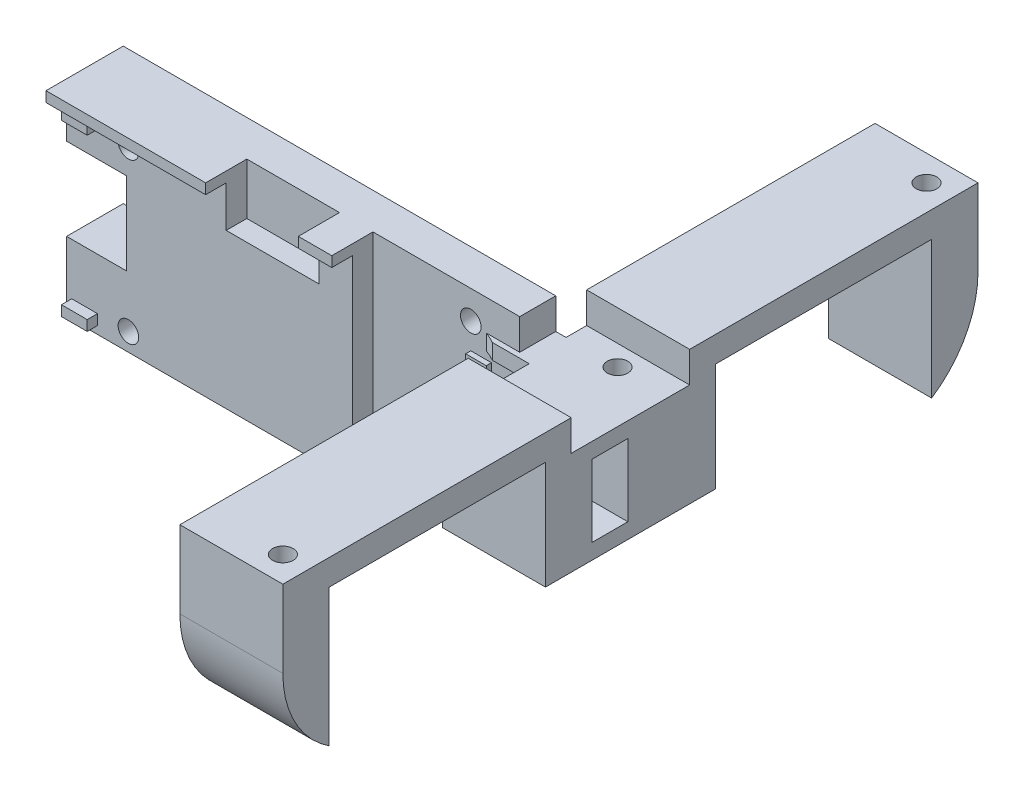
SolidWorks part; units mm, degrees
material "ABS"
ref_plane "Front Plane" through (0, 0, 0) normal (0, 0, 1) x (1, 0, 0)
ref_plane "Top Plane" through (0, 0, 0) normal (0, 1, 0) x (1, 0, 0)
ref_plane "Right Plane" through (0, 0, 0) normal (1, 0, 0) x (0, 0, -1)
sketch "Sketch1" plane through (0, 0, 0) normal (0, 1, 0) x (1, 0, 0)
  line L1 (-40.3176, 43.2333) -> (45.6824, 43.2333)
  line L2 (45.6824, 43.2333) -> (45.6824, -16.7667)
  line L3 (45.6824, -16.7667) -> (65.6824, -16.7667)
  line L4 (65.6824, -16.7667) -> (65.6824, 118.2333)
  line L7 (-40.3176, 43.2333) -> (-40.3176, 58.2333)
  line L8 (-40.3176, 58.2333) -> (45.6824, 58.2333)
  line L9 (45.6824, 58.2333) -> (45.6824, 118.2333)
  line L10 (45.6824, 118.2333) -> (65.6824, 118.2333)
  dimension "D1" = 20
  dimension "D2" = 60
  dimension "D3" = 86
  dimension "D4" = 15
  dimension "D5" = 60
  dimension "D6" = 20
extrude "Boss-Extrude1" add sketch "Sketch1" along normal blind 35
sketch "Sketch2" plane through (65.6824, 0, 0) normal (1, 0, 0) x (0, 0, -1)
  line L1 (-7.7667, 30) -> (34.2333, 30)
  line L2 (-7.7667, 30) -> (-7.7667, 9)
  line L3 (-7.7667, 9) -> (34.2333, 9)
  line L4 (34.2333, 30) -> (34.2333, 9)
  line L5 (-16.7667, 35) -> (-16.7667, 0) construction
  line L6 (50.7333, 24.6294) -> (50.7333, 59.3446) construction
  line L7 (-16.7667, 0) -> (118.2333, 0) construction
  line L9 (109.2333, 9) -> (67.2333, 9)
  line L10 (109.2333, 30) -> (109.2333, 9)
  line L11 (109.2333, 30) -> (67.2333, 30)
  line L12 (67.2333, 30) -> (67.2333, 9)
  dimension "D1" = 21
  dimension "D2" = 42
  dimension "D3" = 9
  dimension "D4" = 9
  dimension "D5" = 7.5
extrude "Cut-Extrude1" cut sketch "Sketch2" against normal up to next
sketch "Sketch3" plane through (45.6824, 0, 0) normal (-1, 0, 0) x (0, 0, 1)
  line L0 (7.7667, 9) -> (7.7667, 30) construction
  line L1 (-34.2333, 9) -> (7.7667, 9) construction
  line L2 (-50.7333, 32.1987) -> (-50.7333, 60.1119) construction
  line L3 (-43.2333, 35) -> (-43.2333, 0) construction
  circle A0 centre (11.2667, 24.75) radius 2
  circle A1 centre (11.2667, 15.25) radius 2
  circle A2 centre (-37.7333, 24.75) radius 2
  circle A3 centre (-37.7333, 15.25) radius 2
  circle A4 centre (-112.7333, 24.75) radius 2
  circle A5 centre (-112.7333, 15.25) radius 2
  circle A6 centre (-63.7333, 15.25) radius 2
  circle A7 centre (-63.7333, 24.75) radius 2
  dimension "D1" = 4
  dimension "D2" = 49
  dimension "D3" = 9.5
  dimension "D4" = 3.5
  dimension "D5" = 6.25
  dimension "D6" = 7.5
extrude "Cut-Extrude2" cut sketch "Sketch3" against normal blind 10
fillet "Fillet1" radius 20 2 edges at (55.6824, 0, 16.7667) (55.6824, 0, -118.2333)
sketch "Sketch6" plane through (65.6824, 0, 0) normal (1, 0, 0) x (0, 0, -1)
  line L0 (34.2333, 9) -> (34.2333, 30) construction
  line L1 (-7.7667, 9) -> (34.2333, 9)
  line L2 (-7.7667, 9) -> (-7.7667, 0)
  line L3 (-7.7667, 0) -> (34.2333, 0)
  line L4 (34.2333, 9) -> (34.2333, 0)
  line L5 (3.2333, 0) -> (98.2333, 0) construction
  line L6 (50.7333, 24.0053) -> (50.7333, 51.0852) construction
  line L7 (67.2333, 9) -> (67.2333, 0)
  line L8 (109.2333, 9) -> (67.2333, 9)
  line L9 (109.2333, 0) -> (67.2333, 0)
  line L10 (109.2333, 9) -> (109.2333, 0)
  dimension "D1" = 7.5
extrude "Cut-Extrude5" cut sketch "Sketch6" against normal up to next
sketch "Sketch8" plane through (0, 0, 0) normal (0, -1, 0) x (1, 0, 0)
  line L1 (45.6824, -67.2333) -> (45.6824, -58.2333) construction
  line L2 (45.6824, -67.2333) -> (65.6824, -67.2333) construction
  line L3 (65.6824, -34.2333) -> (65.6824, -67.2333) construction
  line L4 (45.6824, -34.2333) -> (65.6824, -34.2333) construction
  line L5 (45.6824, -43.2333) -> (45.6824, -34.2333) construction
  line L9 (45.6824, -67.2333) -> (45.6824, -58.2333)
  line L10 (45.6824, -67.2333) -> (65.6824, -67.2333)
  line L11 (65.6824, -34.2333) -> (65.6824, -67.2333)
  line L12 (45.6824, -34.2333) -> (65.6824, -34.2333)
  line L13 (45.6824, -43.2333) -> (45.6824, -34.2333)
  line L16 (45.6824, -43.2333) -> (25.6824, -43.2333)
  line L17 (-40.3176, -43.2333) -> (45.6824, -43.2333) construction
  line L18 (25.6824, -43.2333) -> (25.6824, -58.2333)
  line L19 (45.6824, -58.2333) -> (-40.3176, -58.2333) construction
  line L20 (25.6824, -58.2333) -> (45.6824, -58.2333)
  dimension "D1" = 20
extrude "Cut-Extrude7" cut sketch "Sketch8" against normal blind 9
sketch "Sketch9" plane through (0, 9, 0) normal (0, -1, 0) x (1, 0, 0)
  line L1 (65.6824, -34.2333) -> (45.6824, -34.2333) construction
  line L2 (65.6824, -67.2333) -> (65.6824, -34.2333) construction
  line L3 (45.6824, -67.2333) -> (65.6824, -67.2333) construction
  circle A0 centre (55.6824, -42.2333) radius 2
  circle A1 centre (55.6824, -59.2333) radius 2
  dimension "D4" = 10
  dimension "D5" = 8
  dimension "D6" = 8
extrude "Cut-Extrude8" cut sketch "Sketch9" against normal blind 10
sketch "Sketch10" plane through (0, 35, 0) normal (0, 1, 0) x (1, 0, 0)
  line L0 (45.6824, 62.2333) -> (65.6824, 62.2333)
  line L1 (45.6824, 118.2333) -> (45.6824, 58.2333) construction
  line L2 (65.6824, -16.7667) -> (65.6824, 118.2333) construction
  line L3 (65.6824, 62.2333) -> (65.6824, 39.2333)
  line L4 (65.6824, 39.2333) -> (45.6824, 39.2333)
  line L5 (45.6824, 43.2333) -> (45.6824, -16.7667) construction
  line L7 (45.6824, 39.2333) -> (45.6824, 43.2333)
  line L8 (45.6824, 43.2333) -> (43.6824, 43.2333)
  line L9 (-40.3176, 43.2333) -> (45.6824, 43.2333) construction
  line L10 (43.6824, 43.2333) -> (43.6824, 58.2333)
  line L11 (45.6824, 58.2333) -> (-40.3176, 58.2333) construction
  line L12 (43.6824, 58.2333) -> (45.6824, 58.2333)
  line L13 (45.6824, 58.2333) -> (45.6824, 62.2333)
  dimension "D1" = 5
  dimension "D2" = 5
  dimension "D3" = 2
extrude "Cut-Extrude9" cut sketch "Sketch10" against normal blind 6
sketch "Sketch11" plane through (0, 29, 0) normal (0, 1, 0) x (1, 0, 0)
  line L0 (45.6824, 62.2333) -> (45.6824, 58.2333) construction
  circle A0 centre (55.6824, 58.2333) radius 2
  circle A1 centre (55.6824, 43.2333) radius 2
  dimension "D1" = 4
  dimension "D2" = 10
  dimension "D5" = 0
extrude "Cut-Extrude10" cut sketch "Sketch11" against normal blind 9
sketch "Sketch12" plane through (0, 35, 0) normal (0, 1, 0) x (1, 0, 0)
  line L0 (65.6824, 118.2333) -> (45.6824, 118.2333) construction
  line L1 (45.6824, -16.7667) -> (65.6824, -16.7667) construction
  line L2 (65.6824, -16.7667) -> (65.6824, 39.2333) construction
  line L3 (65.6824, 62.2333) -> (65.6824, 118.2333) construction
  circle A0 centre (60.6824, -11.7667) radius 2
  circle A1 centre (60.6824, 113.2333) radius 2
  dimension "D2" = 4
  dimension "D1" = 5
  dimension "D3" = 5
  dimension "D4" = 5
  dimension "D5" = 5
extrude "Cut-Extrude11" cut sketch "Sketch12" against normal blind 10
sketch "Sketch14" plane through (0, 0, -43.2333) normal (0, 0, 1) x (1, 0, 0)
  line L0 (-40.3176, 35) -> (-40.3176, 0) construction
  line L1 (-40.3176, 33) -> (44.6824, 33)
  line L2 (-40.3176, 33) -> (-40.3176, 0)
  line L3 (-40.3176, 0) -> (44.6824, 0)
  line L4 (44.6824, 33) -> (44.6824, 0)
  line L5 (-40.3176, 0) -> (25.6824, 0) construction
  line L7 (-40.3176, 35) -> (43.6824, 35) construction
  dimension "D1" = 85
  dimension "D2" = 2
extrude "Cut-Extrude13" cut sketch "Sketch14" against normal blind 4
sketch "Sketch15" plane through (0, 0, -47.2333) normal (0, 0, 1) x (1, 0, 0)
  line L1 (15.6824, 20) -> (43.6824, 20)
  line L3 (15.6824, 0) -> (43.6824, 0)
  line L4 (43.6824, 20) -> (43.6824, 0)
  line L5 (43.6824, 29) -> (43.6824, 33) construction
  line L6 (-40.3176, 0) -> (25.6824, 0) construction
  line L13 (15.6824, 20) -> (15.6824, 0)
  line L14 (-40.3176, 33) -> (-40.3176, 0) construction
  point P0 (14.6824, 18.5247)
  point P7 (14.6824, 8)
  point P10 (18.6824, 8)
  point P11 (15.265, 8)
  dimension "D1" = 20
  dimension "D3" = 0
  dimension "D5" = 56
extrude "Cut-Extrude14" cut sketch "Sketch15" against normal blind 4
sketch "Sketch16" plane through (0, 0, 0) normal (0, -1, 0) x (1, 0, 0)
  line L0 (25.6824, -58.2333) -> (-40.3176, -58.2333) construction
  line L1 (-40.3176, -47.2333) -> (39.6824, -47.2333)
  line L2 (-40.3176, -47.2333) -> (-40.3176, -58.2333)
  line L3 (-40.3176, -58.2333) -> (39.6824, -58.2333)
  line L4 (39.6824, -47.2333) -> (39.6824, -58.2333)
  dimension "D1" = 80
extrude "Boss-Extrude2" add sketch "Sketch16" along normal blind 5 and the other way up to surface (9 mm away) other way up to face at (45.1824, 9, -50.2333)
sketch "Sketch13" plane through (0, 0, -43.2333) normal (0, 0, 1) x (1, 0, 0)
  line L1 (-38.3176, 32) -> (36.6824, 32) construction
  line L2 (-38.3176, 32) -> (-38.3176, -4) construction
  line L3 (-38.3176, -4) -> (36.6824, -4) construction
  line L4 (36.6824, 32) -> (36.6824, -4) construction
  line L5 (-40.3176, 33) -> (-40.3176, -5) construction
  line L6 (-40.3176, 35) -> (43.6824, 35) construction
  circle A0 centre (-28.3176, 29.5) radius 2
  circle A1 centre (34.1824, 29.5) radius 2
  circle A2 centre (34.1824, -1.5) radius 2
  circle A3 centre (-28.3176, -1.5) radius 2
  dimension "D3" = 4
  dimension "D1" = 31
  dimension "D2" = 62.5
  dimension "D4" = 75
  dimension "D5" = 36
  dimension "D6" = 2.5
  dimension "D7" = 10
  dimension "D8" = 2
  dimension "D9" = 5.5
extrude "Cut-Extrude12" cut sketch "Sketch13" against normal blind 12
fillet "Fillet2" radius 2 1 edges at (39.6824, -5, -52.7333)
sketch "Sketch17" plane through (0, 0, -43.2333) normal (0, 0, 1) x (1, 0, 0)
  line L1 (43.6824, -5) -> (15.1824, -5)
  line L2 (43.6824, -5) -> (43.6824, 35)
  line L4 (15.1824, -5) -> (15.1824, 35)
  line L5 (-40.3176, 35) -> (43.6824, 35) construction
  line L7 (-9.3176, 35) -> (8.6824, 35)
  line L8 (-9.3176, 35) -> (-9.3176, 25)
  line L9 (-9.3176, 25) -> (8.6824, 25)
  line L10 (8.6824, 35) -> (8.6824, 25)
  line L11 (15.1824, 35) -> (43.6824, 35)
  circle A1 centre (-28.3176, 29.5) radius 2 construction
  point P4 (0, 0)
  point P10 (0, 0)
  point P11 (43.6824, 35)
  point P17 (43.097, 35)
  dimension "D3" = 19
  dimension "D2" = 6.5
  dimension "D4" = 18
  dimension "D5" = 10
  dimension "D6" = 40
extrude "Cut-Extrude15" cut sketch "Sketch17" against normal blind 8
sketch "Sketch20" plane through (0, 0, -47.2333) normal (0, 0, 1) x (1, 0, 0)
  line L0 (-40.3176, 33) -> (-40.3176, -5) construction
  line L1 (-40.3176, 24.5) -> (-32.3176, 24.5)
  line L2 (-40.3176, 24.5) -> (-40.3176, 8.5)
  line L3 (-40.3176, 8.5) -> (-32.3176, 8.5)
  line L4 (-32.3176, 24.5) -> (-32.3176, 8.5)
  circle A0 centre (-28.3176, 29.5) radius 2 construction
  dimension "D1" = 8
  dimension "D2" = 16
  dimension "D3" = 5
extrude "Cut-Extrude18" cut sketch "Sketch20" against normal up to next
sketch "Sketch7" plane through (-40.3176, 0, 0) normal (-1, 0, 0) x (0, 0, 1)
  line L1 (-47.2333, -5) -> (-58.2333, -5) construction
  line L2 (-58.2333, 35) -> (-43.2333, 35) construction
  line L3 (-43.2333, 35) -> (-43.2333, 33) construction
  circle A0 centre (-50.7333, 28.5) radius 2
  circle A1 centre (-50.7333, 5) radius 2
  dimension "D1" = 4
  dimension "D2" = 10
  dimension "D4" = 6.5
  dimension "D5" = 7.5
extrude "Cut-Extrude6" cut sketch "Sketch7" against normal blind 13
chamfer "Chamfer1" distance 10 angle 20 1 edges at (-32.3176, 16.5, -47.2333)
sketch "Sketch21" plane through (0, 0, -47.2333) normal (0, 0, 1) x (1, 0, 0)
  line L0 (-38.3176, 32) -> (36.6824, 32) construction
  line L1 (-38.3176, 32) -> (-38.3176, -4) construction
  line L2 (-38.3176, -4) -> (36.6824, -4) construction
  line L3 (36.6824, 32) -> (36.6824, -4) construction
  line L5 (33.1824, 26.5) -> (39.1824, 26.5) construction
  line L6 (33.1824, 26.5) -> (33.1824, 14) construction
  line L7 (33.1824, 14) -> (39.1824, 14)
  line L8 (39.1824, 26.5) -> (39.1824, 14) construction
  line L9 (32.6824, 13) -> (37.6824, 13) construction
  line L10 (32.6824, 13) -> (32.6824, 3) construction
  line L11 (32.6824, 3) -> (37.6824, 3) construction
  line L12 (37.6824, 13) -> (37.6824, 3) construction
  circle A0 centre (-28.3176, 29.5) radius 2
  circle A1 centre (34.1824, 29.5) radius 2
  circle A2 centre (34.1824, -1.5) radius 2
  circle A3 centre (-28.3176, -1.5) radius 2
  dimension "D3" = 4
  dimension "D1" = 31
  dimension "D2" = 62.5
  dimension "D4" = 75
  dimension "D5" = 36
  dimension "D6" = 2.5
  dimension "D7" = 10
  dimension "D8" = 12.5
  dimension "D9" = 6
  dimension "D10" = 3.5
  dimension "D11" = 5.5
  dimension "D12" = 5
  dimension "D13" = 10
  dimension "D14" = 7
  dimension "D15" = 1
sketch "Sketch22" plane through (65.6824, 0, 0) normal (1, 0, 0) x (0, 0, -1)
  line L0 (39.2333, 29) -> (62.2333, 29) construction
  line L1 (43.2333, 26) -> (50.2333, 26)
  line L2 (43.2333, 26) -> (43.2333, 12)
  line L3 (43.2333, 12) -> (50.2333, 12)
  line L4 (50.2333, 26) -> (50.2333, 12)
  line L5 (39.2333, 29) -> (39.2333, 35) construction
  dimension "D1" = 14
  dimension "D2" = 3
  dimension "D3" = 4
  dimension "D4" = 7
extrude "Cut-Extrude19" cut sketch "Sketch22" against normal up to next
sketch "Sketch24" plane through (0, 29, 0) normal (0, 1, 0) x (1, 0, 0)
  line L0 (43.6824, 51.2333) -> (15.1824, 51.2333) construction
  line L1 (45.6824, 39.2333) -> (45.6824, -16.7667) construction
  line L2 (43.6824, 51.2333) -> (43.6824, 47.2333) construction
  line L3 (37.1824, 51.2333) -> (45.6824, 51.2333)
  line L4 (45.6824, 51.2333) -> (45.6824, 39.2333)
  arc A0 (37.1824, 51.2333) -> (45.6824, 39.2333) centre (32.9618, 39.2333) cw
  dimension "D1" = 6.5
extrude "Boss-Extrude4" add sketch "Sketch24" against normal up to surface (3 mm away) up to face at (51.6824, 26, -45.8999)
sketch "Sketch25" plane through (0, 9, 0) normal (0, -1, 0) x (1, 0, 0)
  line L0 (45.6824, -34.2333) -> (45.6824, -43.2333) construction
  line L1 (37.1824, -51.2333) -> (45.6824, -51.2333)
  line L2 (45.6824, -51.2333) -> (45.6824, -39.2333)
  arc A1 (37.1824, -51.2333) -> (45.6824, -39.2333) centre (32.9618, -39.2333) ccw
  arc A2 (45.0371, -43.2333) -> (45.6824, -39.2333) centre (32.9618, -39.2333) ccw construction
extrude "Boss-Extrude5" add sketch "Sketch25" against normal up to surface (3 mm away) up to face at (51.6824, 12, -45.7888)
sketch "Sketch26" plane through (0, 29, 0) normal (0, 1, 0) x (1, 0, 0)
  line L0 (45.2398, 42.5597) -> (43.6861, 42.5597)
  line L1 (43.6861, 42.5597) -> (44.0632, 45.4438)
  arc A0 (44.0632, 45.4438) -> (45.2398, 42.5597) centre (32.9618, 39.2333) cw
  arc A1 (44.6824, 44.1771) -> (37.1824, 51.2333) centre (32.9618, 39.2333) ccw construction
  arc A2 (45.6824, 39.2333) -> (45.0371, 43.2333) centre (32.9618, 39.2333) ccw construction
extrude "Cut-Extrude21" cut sketch "Sketch26" against normal through all
sketch "Sketch27" plane through (0, 29, 0) normal (0, 1, 0) x (1, 0, 0)
  line L0 (43.6824, 51.2333) -> (15.1824, 51.2333) construction
  line L1 (39.3503, 50.2333) -> (46.5255, 50.2333)
  line L2 (39.3503, 50.2333) -> (39.3503, 41.2333)
  line L3 (39.3503, 41.2333) -> (46.5255, 41.2333)
  line L4 (46.5255, 50.2333) -> (46.5255, 41.2333)
  arc A0 (45.6824, 39.2333) -> (37.1824, 51.2333) centre (32.9618, 39.2333) ccw construction
  dimension "D1" = 9
  dimension "D2" = 1
extrude "Cut-Extrude22" cut sketch "Sketch27" against normal through all
sketch "Sketch28" plane through (0, 0, -47.2333) normal (0, 0, 1) x (1, 0, 0)
  line L0 (-9.3176, 33) -> (-40.3176, 33) construction
  line L1 (-39.3176, 31.5) -> (-34.3176, 31.5)
  line L2 (-39.3176, 31.5) -> (-39.3176, 29.5)
  line L3 (-39.3176, 29.5) -> (-34.3176, 29.5)
  line L4 (-34.3176, 31.5) -> (-34.3176, 29.5)
  line L5 (-39.3176, -1.5) -> (-34.3176, -1.5)
  line L6 (-39.3176, -1.5) -> (-39.3176, -3.5)
  line L7 (-39.3176, -3.5) -> (-34.3176, -3.5)
  line L8 (-34.3176, -1.5) -> (-34.3176, -3.5)
  line L9 (15.1824, -5) -> (-40.3176, -5) construction
  line L10 (-40.3176, 8.5) -> (-40.3176, -5) construction
  line L11 (-40.3176, 33) -> (-40.3176, 24.5) construction
  dimension "D1" = 2
  dimension "D2" = 2
  dimension "D3" = 5
  dimension "D4" = 5
  dimension "D5" = 1.5
  dimension "D6" = 1.5
  dimension "D7" = 1
  dimension "D8" = 1
extrude "Boss-Extrude6" add sketch "Sketch28" along normal blind 2
sketch "Sketch29" plane through (0, 0, -51.2333) normal (0, 0, 1) x (1, 0, 0)
  line L0 (43.6824, 35) -> (15.1824, 35) construction
  line L1 (34.1824, 24.5) -> (38.1824, 24.5)
  line L2 (34.1824, 24.5) -> (34.1824, 16.5)
  line L3 (34.1824, 16.5) -> (38.1824, 16.5)
  line L4 (38.1824, 24.5) -> (38.1824, 16.5)
  line L5 (15.1824, 33) -> (15.1824, -5) construction
  dimension "D1" = 4
  dimension "D2" = 8
  dimension "D3" = 19
  dimension "D4" = 10.5
extrude "Boss-Extrude7" add sketch "Sketch29" along normal blind 1
sketch "Sketch30" plane through (0, 0, -51.2333) normal (0, 0, 1) x (1, 0, 0)
  line L0 (15.1824, -5) -> (37.6824, -5) construction
  line L1 (33.6824, 11.5) -> (36.6824, 11.5)
  line L2 (33.6824, 11.5) -> (33.6824, 4.5)
  line L3 (33.6824, 4.5) -> (36.6824, 4.5)
  line L4 (36.6824, 11.5) -> (36.6824, 4.5)
  line L5 (39.6824, -3) -> (39.6824, 9) construction
  dimension "D1" = 7
  dimension "D2" = 3
  dimension "D3" = 9.5
  dimension "D4" = 3
extrude "Boss-Extrude8" add sketch "Sketch30" along normal blind 2
